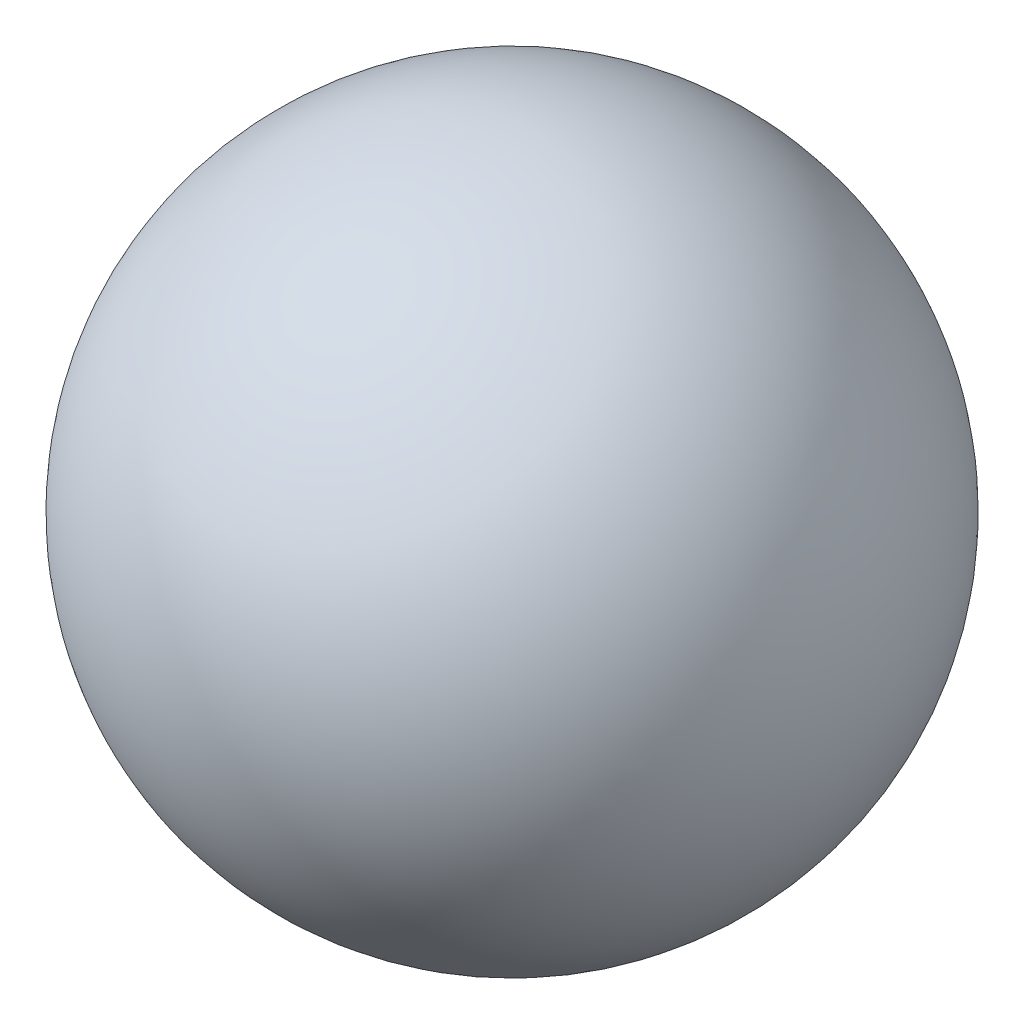
SolidWorks part; units mm, degrees
ref_plane "Front Plane" through (0, 0, 0) normal (0, 0, 1) x (1, 0, 0)
ref_plane "Top Plane" through (0, 0, 0) normal (0, 1, 0) x (1, 0, 0)
ref_plane "Right Plane" through (0, 0, 0) normal (1, 0, 0) x (0, 0, -1)
sketch "Sketch1" plane through (0, 0, 0) normal (0, 1, 0) x (1, 0, 0)
  line L0 (0, -95) -> (0, 95) construction
  line L1 (0, 95) -> (0, -95)
  arc A0 (0, -95) -> (0, 95) centre (0, 0) ccw
  point P6 (0, 0)
  dimension "D1" = 190
revolve "Revolve1" add sketch "Sketch1" angle 360 about L0
